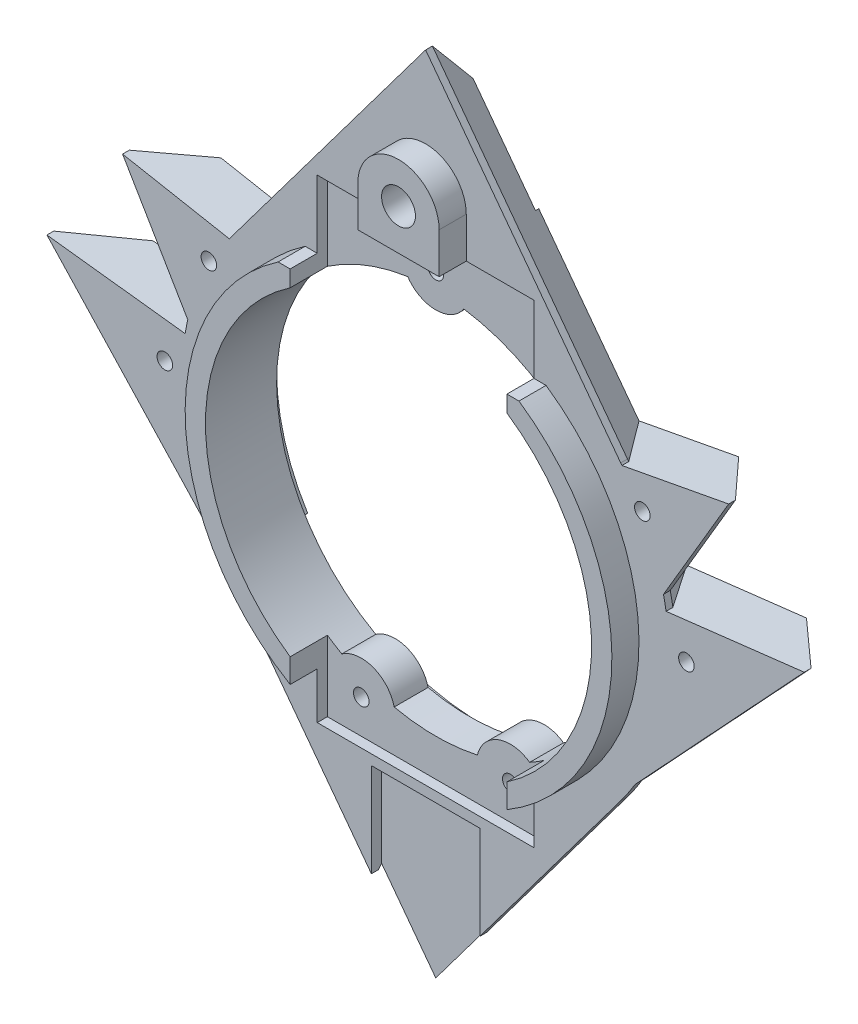
SolidWorks part; units mm, degrees
ref_plane "Спереди" through (0, 0, 0) normal (0, 0, 1) x (1, 0, 0)
ref_plane "Сверху" through (0, 0, 0) normal (0, 1, 0) x (1, 0, 0)
ref_plane "Справа" through (0, 0, 0) normal (1, 0, 0) x (0, 0, -1)
sketch "Эскиз1" plane through (0, 0, 0) normal (0, 0, 1) x (1, 0, 0)
  line L8 (0, 60) -> (28.8, 21.6)
  line L9 (0, -60) -> (28.8, -21.6)
  line L10 (-28.8, 21.6) -> (0, 60)
  line L11 (-28.8, -21.6) -> (0, -60)
  circle A0 centre (0, 0) radius 28.5
  arc A2 (28.8, 21.6) -> (28.8, -21.6) centre (0, 0) cw
  arc A3 (-28.8, 21.6) -> (-28.8, -21.6) centre (0, 0) ccw
  circle A6 centre (0, 31) radius 5
  circle A7 centre (-11, -29) radius 5
  circle A8 centre (11, -29) radius 5
  point P3 (-11, -29)
  point P4 (11, -29)
  point P15 (0, 60)
  point P16 (0, -60)
  dimension "D1" = 57
  dimension "D2" = 31
  dimension "D7" = 36
  dimension "D3" = 10
  dimension "D4" = 29
  dimension "D5" = 11
  dimension "D6" = 11
  dimension "D8" = 60
  dimension "D9" = 60
extrude "Бобышка-Вытянуть1" add sketch "Эскиз1" along normal blind 8
chamfer "Фаска12" distance 7 distance2 5 6 edges at (-14.4, -40.8, 0) (14.4, -40.8, 0) (36, 0, 0) (-36, 0, 0) (-14.4, 40.8, 0) (14.4, 40.8, 0)
sketch "Эскиз11" plane through (0, 0, 0) normal (0, 0, -1) x (-1, 0, 0)
  circle A0 centre (0, 0) radius 30
  dimension "D1" = 60
extrude "Вырез-Вытянуть1" cut sketch "Эскиз11" against normal blind 1.5
sketch "Эскиз17" plane through (0, 0, 8) normal (0, 0, -1) x (-1, 0, 0)
  line L0 (28.9026, -20.6129) -> (55.9026, 8.3871)
  line L1 (55.9026, 8.3871) -> (30.5283, 5.3871)
  line L3 (34.7383, 7.3143) -> (44.7383, 24.3143)
  line L4 (44.7383, 24.3143) -> (23.4165, 20.3143)
  line L5 (25.2389, -18) -> (28.9026, -20.6129)
  line L6 (34.7383, 7.3143) -> (30.3349, 6.3871)
  line L7 (-30.3349, 6.3871) -> (-34.7383, 7.3143)
  line L8 (-34.7383, 7.3143) -> (-44.7383, 24.3143)
  line L9 (-44.7383, 24.3143) -> (-23.4165, 20.3143)
  line L10 (-30.5283, 5.3871) -> (-55.9026, 8.3871)
  line L11 (-55.9026, 8.3871) -> (-28.9026, -20.6129)
  line L12 (-28.9026, -20.6129) -> (-25.2389, -18)
  circle A3 centre (0, 0) radius 31
  line M61 (0, 60) -> (28.8, 21.6)
  arc M62 (28.8, 21.6) -> (28.8, -21.6) centre (0, 0) cw
  line M64 (0, -60) -> (-28.8, -21.6)
  arc M65 (-28.8, -21.6) -> (-28.8, 21.6) centre (0, 0) cw
  dimension "D11" = 62
  dimension "D2" = 18
  dimension "D8" = 1
  dimension "D12" = 4.5
  dimension "D13" = 4
  dimension "D14" = 3
  dimension "D15" = 29
  dimension "D16" = 17
  dimension "D17" = 27
  dimension "D18" = 10
extrude "Бобышка-Вытянуть5" add sketch "Эскиз17" along normal up to surface (8 mm away) separate body contours L8 L9 M65 | L9 A3 L7 M65 | L11 L10 M65 M64 | L10 A3 L12 L11 M64 M65 | L5 A3 L1 M62 | L5 L1 L0 M62 | L3 L6 L4 M62 M61 | L6 A3 L4 M61 M62
chamfer "Фаска13" distance 5 distance2 7 1 edges at (-42.4026, -6.1129, 0)
chamfer "Фаска14" distance 5 distance2 7 1 edges at (42.4026, -6.1129, 0)
chamfer "Фаска15" distance 7 distance2 5 1 edges at (39.7383, 15.8143, 0)
chamfer "Фаска16" distance 5 distance2 7 1 edges at (-39.7383, 15.8143, 0)
combine bodies "Соединить2" operation type add bodies to combine 131 129 122 128 113
sketch "Эскиз23" plane through (0, 0, 8) normal (0, 0, 1) x (1, 0, 0)
  line L7 (-35, 36) -> (35, 36)
  line L8 (-35, 36) -> (-35, 28)
  line L9 (-35, 28) -> (35, 28)
  line L10 (35, 36) -> (35, 28)
  line L11 (-35, 36) -> (35, 28) construction
  line L12 (-35, 28) -> (35, 36) construction
  line L13 (-16, -34) -> (16, -34)
  line L14 (-16, -34) -> (-16, 36)
  line L15 (-16, 36) -> (16, 36)
  line L16 (16, -34) -> (16, 36)
  point P6 (0, 32)
  point P15 (0, 36)
  dimension "D1" = 36
  dimension "D3" = 70
  dimension "D4" = 8
  dimension "D5" = 70
  dimension "D6" = 32
extrude "Вырез-Вытянуть7" cut sketch "Эскиз23" against normal blind 1.5
sketch "Эскиз13" plane through (0, 0, 8) normal (0, 0, 1) x (1, 0, 0)
  line L1 (-8, -34) -> (8, -34)
  line L2 (-8, -34) -> (-8, -60)
  line L3 (-8, -60) -> (8, -60)
  line L4 (8, -34) -> (8, -60)
  point P5 (0, -60)
  dimension "D1" = 16
  dimension "D2" = 60
  dimension "D3" = 34
extrude "Вырез-Вытянуть2" cut sketch "Эскиз13" against normal blind 1.5
sketch "Эскиз8" plane through (0, 0, 6.5) normal (0, 0, 1) x (1, 0, 0)
  line L5 (-15, -35) -> (15, -35)
  line L6 (-15, -35) -> (-15, 35)
  line L7 (-15, 35) -> (15, 35)
  line L8 (15, -35) -> (15, 35)
  line L9 (-15, -35) -> (15, 35) construction
  line L10 (-15, 35) -> (15, -35) construction
  point P1 (0, 31)
  point P2 (-11, -29)
  point P3 (11, -29)
  point P12 (0, 0)
  dimension "D1" = 6
  dimension "D2" = 4
  dimension "D3" = 4
  dimension "D4" = 4
  dimension "D5" = 30
  dimension "D6" = 70
sketch "Эскиз15" plane through (0, 0, 0) normal (0, 0, -1) x (-1, 0, 0)
  circle A0 centre (0, -40) radius 17.5
  circle A1 centre (0, -40) radius 35
  dimension "D2" = 35
  dimension "D3" = 70
  dimension "D1" = 40
sketch "Эскиз18" plane through (0, 0, 0) normal (0, 0, -1) x (-1, 0, 0)
  line L8 (-12.5326, 43.2898) -> (0, 60)
  line L9 (0, 60) -> (12.5326, 43.2898)
  line L10 (0, 60) -> (28.8, 21.6) construction
  line L11 (-28.8, 21.6) -> (0, 60) construction
  arc A4 (1.5, 29.9625) -> (-1.5, 29.9625) centre (0, 0) ccw
  circle A5 centre (0, 0) radius 30 construction
  circle A6 centre (0, 0) radius 30 construction
  arc A7 (1.5, 29.9625) -> (12.5326, 43.2898) centre (33.1405, 15) cw
  arc A8 (-1.5, 29.9625) -> (-12.5326, 43.2898) centre (-33.1405, 15) ccw
  point P10 (0, 30)
  point P13 (0, 0)
  point P16 (0, 0)
  point P17 (0, 0)
  point P18 (13.3482, 42.2024)
  point P22 (-16.2495, 38.3341)
  point P27 (-36.42, 32.6744)
  dimension "D1" = 3
  dimension "D3" = 35
  dimension "D2" = 60
  dimension "D4" = 15
hole_wizard "Сверло под метчик  спиральное M2.24" positions "Эскиз26" profile "Эскиз27" hole size "M2.2x0.45" standard "DIN"
sketch "Эскиз26" plane through (0, 0, 6.5) normal (0, 0, 1) x (1, 0, 0)
  point P0 (0, 31)
  point P3 (-11, -29)
  point P6 (11, -29)
sketch "Эскиз27" plane through (0, 31, 6.5) normal (1, 0, 0) x (0, -1, 0)
  line L0 (0, 0) -> (0, 4.191)
  line L1 (0, 4.191) -> (1.15, 3.5)
  line L2 (1.15, 3.5) -> (1.15, 0)
  line L5 (1.15, 0) -> (0, 0)
  line L10 (0, 4.191) -> (-1.15, 3.5) construction
  line L11 (0, -6.35) -> (0, 107.95) construction
  dimension "Диаметр отверстия" = 2.3
  dimension "Глубина отверстия" = 3.5
  dimension "Угол заточки сверла" = 118
sketch "Эскиз28" plane through (0, 0, 8) normal (0, 0, 1) x (1, 0, 0)
  line L2 (-16, 36) -> (16, 36)
  line L3 (-16, 36) -> (-16, -34)
  line L4 (-16, -34) -> (16, -34)
  line L5 (16, 36) -> (16, -34)
  line L6 (-17.7834, 26) -> (17.7834, 26)
  circle A1 centre (0, 0) radius 28.5
  circle A2 centre (0, 0) radius 31.5
  point P11 (0, 36)
  arc M4 (-16, -23.585) -> (-16, 23.585) centre (0, 0) cw
  line M5 (-16, 23.585) -> (-16, 36)
  arc M8 (16, 23.585) -> (16, -23.585) centre (0, 0) cw
  line M9 (16, -23.585) -> (16, -34)
  dimension "D1" = 3
  dimension "D2" = 57
  dimension "D3" = 32
  dimension "D4" = 70
  dimension "D5" = 36
  dimension "D6" = 26
extrude "Бобышка-Вытянуть6" add sketch "Эскиз28" along normal blind 4 contours A2 L3 M5 M4 | A2 L5 M9 M8
sketch "Эскиз29" plane through (0, 0, 8) normal (0, 0, 1) x (1, 0, 0)
  line L0 (-32, 17) -> (32, 17) construction
  line L1 (-38.5, 1) -> (38.5, 1) construction
  circle A0 centre (-32, 17) radius 3
  circle A1 centre (-38.5, 1) radius 3
  circle A2 centre (32, 17) radius 3
  circle A3 centre (38.5, 1) radius 3
  point P0 (-32, 17)
  point P1 (32, 17)
  point P2 (38.5, 1)
  point P3 (-38.5, 1)
  point P8 (0, 17)
  point P9 (0, 1)
  dimension "D2" = 6
  dimension "D1" = 32
  dimension "D3" = 38.5
  dimension "D4" = 1
  dimension "D5" = 17
hole_wizard "Сверло под метчик  спиральное M2.25" positions "Эскиз30" profile "Эскиз31" hole size "M2.2x0.45" standard "DIN"
sketch "Эскиз30" plane through (0, 0, 8) normal (0, 0, 1) x (1, 0, 0)
  point P0 (-32, 17)
  point P3 (-38.5, 1)
  point P6 (32, 17)
  point P9 (38.5, 1)
sketch "Эскиз31" plane through (-32, 17, 8) normal (1, 0, 0) x (0, -1, 0)
  line L0 (0, 0) -> (0, 4.691)
  line L1 (0, 4.691) -> (1.15, 4)
  line L2 (1.15, 4) -> (1.15, 0)
  line L5 (1.15, 0) -> (0, 0)
  line L10 (0, 4.691) -> (-1.15, 4) construction
  line L11 (0, -6.35) -> (0, 107.95) construction
  dimension "Диаметр отверстия" = 2.3
  dimension "Глубина отверстия" = 4
  dimension "Угол заточки сверла" = 118
sketch "Эскиз32" plane through (0, 0, 0) normal (0, 0, -1) x (-1, 0, 0)
  circle A0 centre (0, 42) radius 2.5
  dimension "D2" = 5
  dimension "D1" = 18
extrude "Вырез-Вытянуть8" cut sketch "Эскиз32" against normal through all both
chamfer "Фаска17" [suppressed] distance 3.5 angle 45
sketch "Эскиз33" plane through (0, 0, 6.5) normal (0, 0, 1) x (1, 0, 0)
  line L0 (8, -49.3333) -> (8, -34) construction
  line L1 (-8, -34) -> (8, -34)
  line L2 (-8, -34) -> (-8, -35.5)
  line L3 (-8, -35.5) -> (8, -35.5)
  line L4 (8, -34) -> (8, -35.5)
  dimension "D1" = 1.5
extrude "Бобышка-Вытянуть7" add sketch "Эскиз33" along normal up to surface (1.5 mm away) up to face at (2.5, 42, 8)
sketch "Эскиз34" plane through (0, 0, 8) normal (0, 0, 1) x (1, 0, 0)
  line L0 (-16, 36) -> (16, 36) construction
  line L1 (-6, 48) -> (6, 48)
  line L2 (-6, 48) -> (-6, 36)
  line L4 (-6, 36) -> (6, 36)
  line L5 (6, 48) -> (6, 36)
  circle A1 centre (0, 42) radius 6
  point P10 (0, 36)
  circle M28 centre (0, 42) radius 2.5
  line M41 (-16, 36) -> (16, 36)
  dimension "D1" = 12
extrude "Бобышка-Вытянуть8" add sketch "Эскиз34" along normal blind 4 contours A1 M28 | A1 L4 L5 | A1 L2 M41
extrude "Вырез-Вытянуть9" cut sketch "Эскиз18" against normal blind 1
extrude "Вырез-Вытянуть10" cut sketch "Эскиз15" against normal blind 1
chamfer "Фаска18" distance 1.5 angle 45 1 edges at (2.5, 42, 1)
